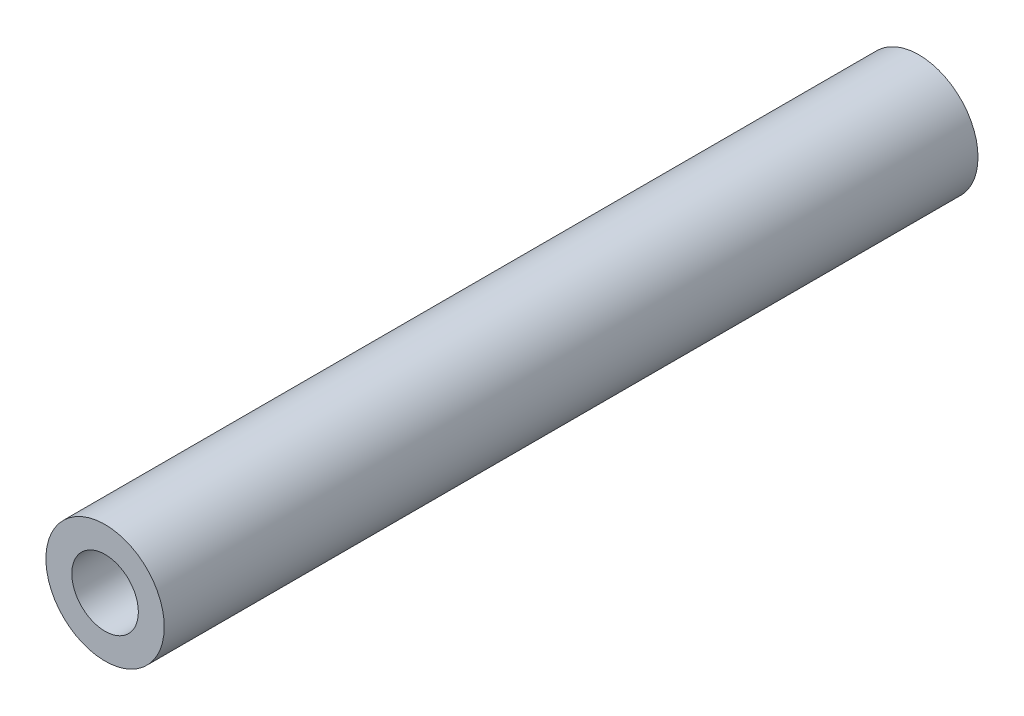
SolidWorks part; units mm, degrees
ref_plane "Спереди" through (0, 0, 0) normal (0, 0, 1) x (1, 0, 0)
ref_plane "Сверху" through (0, 0, 0) normal (0, 1, 0) x (1, 0, 0)
ref_plane "Справа" through (0, 0, 0) normal (1, 0, 0) x (0, 0, -1)
sketch "Эскиз1" plane through (0, 0, 0) normal (0, 0, 1) x (1, 0, 0)
  circle A0 centre (0, 0) radius 4
  circle A1 centre (0, 0) radius 2.25
extrude "Tie_tube" add sketch "Эскиз1" along normal blind 55 from offset 27
